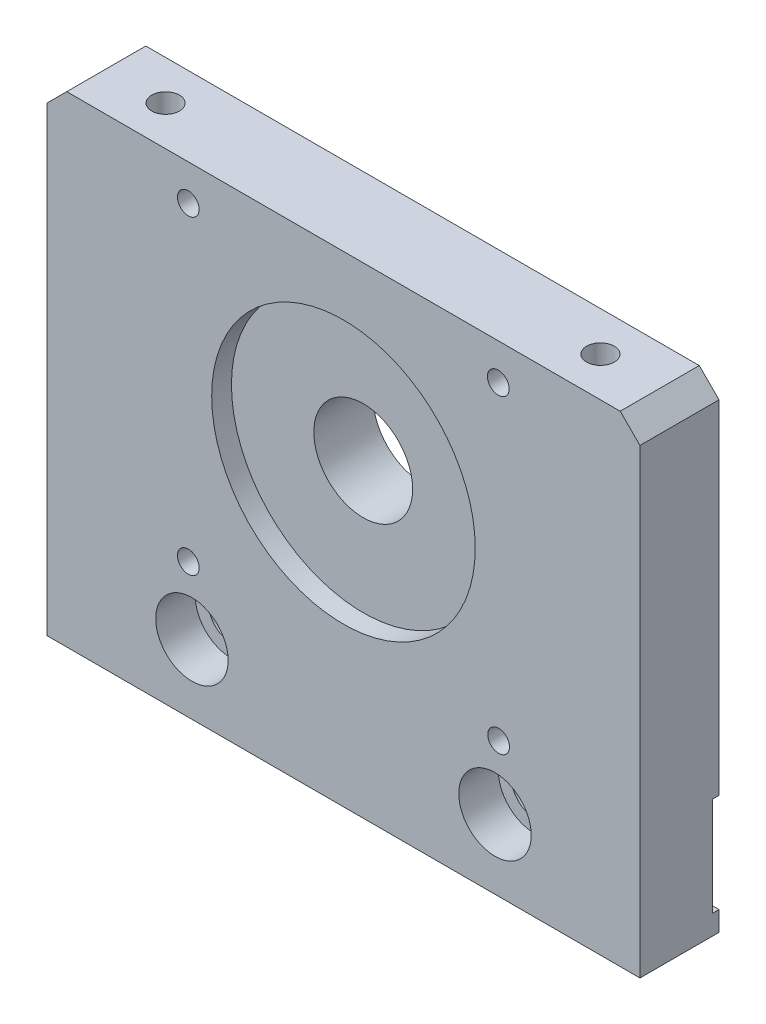
SolidWorks part; units mm, degrees
material "S45C表面镀硬铬"
ref_plane "前基準面" through (0, 0, 0) normal (0, 0, 1) x (1, 0, 0)
ref_plane "上基準面" through (0, 0, 0) normal (0, 1, 0) x (1, 0, 0)
ref_plane "右基準面" through (0, 0, 0) normal (1, 0, 0) x (0, 0, -1)
sketch "草图1" plane through (0, 0, 0) normal (0, 0, 1) x (1, 0, 0)
  line L1 (0, 0) -> (90, 0)
  line L2 (0, 0) -> (0, 73)
  line L3 (0, 73) -> (90, 73)
  line L4 (90, 0) -> (90, 73)
  dimension "D1" = 90
  dimension "D2" = 73
extrude "凸台-拉伸1" add sketch "草图1" along normal blind 12
sketch "草图2" plane through (0, 0, 12) normal (0, 0, 1) x (1, 0, 0)
  line L0 (45, 73) -> (45, 1.2603) construction
  line L1 (90, 73) -> (0, 73) construction
  line L2 (0, 0) -> (90, 0) construction
  circle A0 centre (45, 44) radius 20
  dimension "D1" = 44
  dimension "D2" = 40
extrude "切除-拉伸1" cut sketch "草图2" against normal blind 3
sketch "草图3" plane through (0, 0, 9) normal (0, 0, 1) x (1, 0, 0)
  circle A0 centre (45, 44) radius 7.5
  dimension "D1" = 15
extrude "切除-拉伸2" cut sketch "草图3" against normal through all
chamfer "倒角1" distance 3 angle 45 2 edges at (0, 73, 6) (90, 73, 6)
sketch "草图4" plane through (90, 0, 0) normal (1, 0, 0) x (0, 0, -1)
  line L0 (0, 0) -> (0, 70) construction
  line L1 (0, 3) -> (-1, 3)
  line L2 (0, 3) -> (0, 18)
  line L3 (0, 18) -> (-1, 18)
  line L4 (-1, 3) -> (-1, 18)
  line L5 (-12, 0) -> (0, 0) construction
  dimension "D1" = 1
  dimension "D2" = 3
  dimension "D3" = 15
extrude "切除-拉伸3" cut sketch "草图4" against normal through all
hole_wizard "M6 六角凹头螺钉的柱形沉头孔1" positions "草图6" profile "草图5" counterbore size "M6" standard "ISO" end condition through all
sketch "草图6" plane through (0, 0, 12) normal (0, 0, 1) x (1, 0, 0)
  line L0 (45, 0) -> (45, 21.4776) construction
  line L1 (0, 0) -> (90, 0) construction
  point P0 (22, 10.5)
  point P1 (68, 10.5)
  dimension "D1" = 10.5
  dimension "D2" = 46
sketch "草图5" plane through (22, 10.5, 12) normal (1, 0, 0) x (0, -1, 0)
  line L0 (0, 0) -> (0, 12)
  line L1 (0, 12) -> (3.5, 12)
  line L3 (3.5, 12) -> (3.5, 6)
  line L4 (3.5, 6) -> (5.5, 6)
  line L5 (5.5, 6) -> (5.5, 0)
  line L7 (5.5, 0) -> (0, 0)
  line L11 (0, -6.35) -> (0, 107.95) construction
  dimension "通孔孔直径" = 7
  dimension "通孔孔深度" = 12
  dimension "柱形沉头孔直径" = 11
  dimension "柱形沉头孔深度" = 6
hole_wizard "M5 螺纹孔1" positions "草图8" profile "草图7" tap size "M5" standard "ISO"
sketch "草图8" plane through (0, 73, 0) normal (0, 1, 0) x (-1, 0, 0)
  line L0 (-45, 0) -> (-45, 12) construction
  line L1 (-87, 0) -> (-3, 0) construction
  line L2 (-87, 12) -> (-3, 12) construction
  point P0 (-12, 6)
  point P4 (-78, 6)
sketch "草图7" plane through (12, 73, 6) normal (1, 0, 0) x (0, 0, 1)
  line L0 (0, 0) -> (0, 13.6618)
  line L1 (0, 13.6618) -> (2.1, 12.4)
  line L2 (2.1, 12.4) -> (2.1, 0)
  line L5 (2.1, 0) -> (0, 0)
  line L10 (0, 13.6618) -> (-2.1, 12.4) construction
  line L11 (0, -6.35) -> (0, 107.95) construction
  dimension "螺纹孔钻头直径" = 4.2
  dimension "螺纹孔钻头深度" = 12.4
  dimension "导头角度" = 118
cosmetic thread "孔螺蚊线1" parameters "D1"=10, "D2"=5
cosmetic thread "孔螺蚊线7" parameters "D1"=10, "D2"=5
hole_wizard "M4 螺纹孔1" positions "草图10" profile "草图9" tap size "M4" standard "ISO"
sketch "草图10" plane through (0, 0, 12) normal (0, 0, 1) x (1, 0, 0)
  point P0 (68.5, 67.5)
  point P6 (21.45, 67.55)
  point P9 (21.45, 20.45)
  point P12 (68.55, 20.45)
sketch "草图9" plane through (68.5, 67.5, 12) normal (1, 0, 0) x (0, -1, 0)
  line L0 (0, 0) -> (0, 11.0914)
  line L1 (0, 11.0914) -> (1.65, 10.1)
  line L2 (1.65, 10.1) -> (1.65, 0)
  line L5 (1.65, 0) -> (0, 0)
  line L10 (0, 11.0914) -> (-1.65, 10.1) construction
  line L11 (0, -6.35) -> (0, 107.95) construction
  dimension "螺纹孔钻头直径" = 3.3
  dimension "螺纹孔钻头深度" = 10.1
  dimension "导头角度" = 118
cosmetic thread "孔螺蚊线2" parameters "D1"=8, "D2"=4
cosmetic thread "孔螺蚊线3" parameters "D1"=8, "D2"=4
cosmetic thread "孔螺蚊线4" parameters "D1"=8, "D2"=4
cosmetic thread "孔螺蚊线5" parameters "D1"=8, "D2"=4
hole_wizard "M5 螺纹孔2" positions "草图12" profile "草图11" tap size "M5" standard "ISO"
sketch "草图12" plane through (0, 0, 0) normal (-1, 0, 0) x (0, 0, 1)
  point P0 (6, 43)
sketch "草图11" plane through (0, 43, 6) normal (0, 1, 0) x (0, 0, 1)
  line L0 (0, 0) -> (0, 13.6618)
  line L1 (0, 13.6618) -> (2.1, 12.4)
  line L2 (2.1, 12.4) -> (2.1, 0)
  line L5 (2.1, 0) -> (0, 0)
  line L10 (0, 13.6618) -> (-2.1, 12.4) construction
  line L11 (0, -6.35) -> (0, 107.95) construction
  dimension "螺纹孔钻头直径" = 4.2
  dimension "螺纹孔钻头深度" = 12.4
  dimension "导头角度" = 118
cosmetic thread "孔螺蚊线6" parameters "D1"=10, "D2"=5
